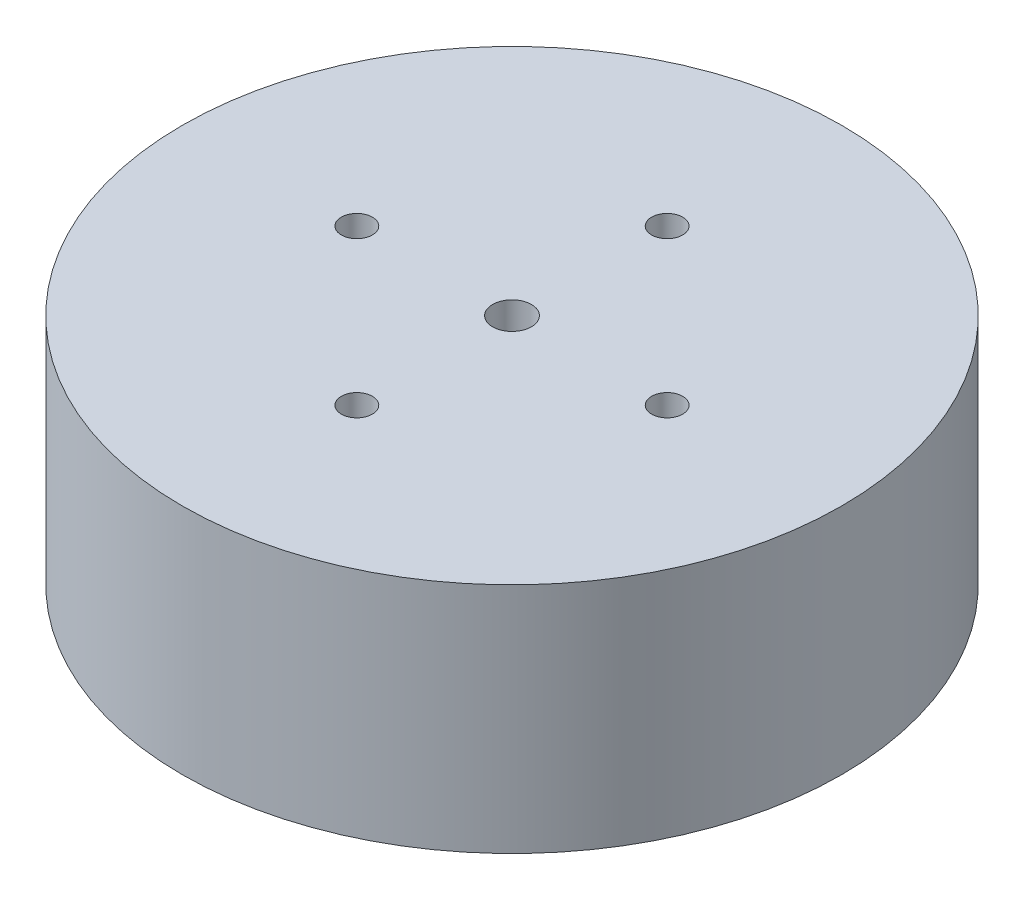
SolidWorks part; units mm, degrees
material "ABS"
ref_plane "Alzado" through (0, 0, 0) normal (0, 0, 1) x (1, 0, 0)
ref_plane "Planta" through (0, 0, 0) normal (0, 1, 0) x (1, 0, 0)
ref_plane "Vista lateral" through (0, 0, 0) normal (1, 0, 0) x (0, 0, -1)
sketch "Croquis1" plane through (0, 0, 0) normal (0, 1, 0) x (1, 0, 0)
  circle A0 centre (0, 0) radius 42.5
  dimension "D1" = 85
extrude "Saliente-Extruir1" add sketch "Croquis1" along normal blind 30
sketch "Croquis2" plane through (0, 30, 0) normal (0, 1, 0) x (1, 0, 0)
  circle A0 centre (0, 0) radius 2.5
  dimension "D1" = 5
extrude "Cortar-Extruir1" cut sketch "Croquis2" against normal blind 10
sketch "Croquis3" plane through (0, 0, 0) normal (0, -1, 0) x (1, 0, 0)
  circle A0 centre (0, 0) radius 27.5
  dimension "D1" = 55
extrude "Cortar-Extruir2" cut sketch "Croquis3" against normal blind 5
sketch "Croquis4" plane through (0, 5, 0) normal (0, -1, 0) x (1, 0, 0)
  circle A0 centre (0, 20) radius 2
  circle A1 centre (-20, 0) radius 2
  circle A2 centre (0, -20) radius 2
  circle A3 centre (20, 0) radius 2
  dimension "D1" = 4
  dimension "D2" = 4
  dimension "D3" = 4
  dimension "D4" = 4
  dimension "D5" = 20
  dimension "D6" = 20
  dimension "D7" = 20
  dimension "D8" = 20
extrude "Cortar-Extruir3" cut sketch "Croquis4" against normal through all
